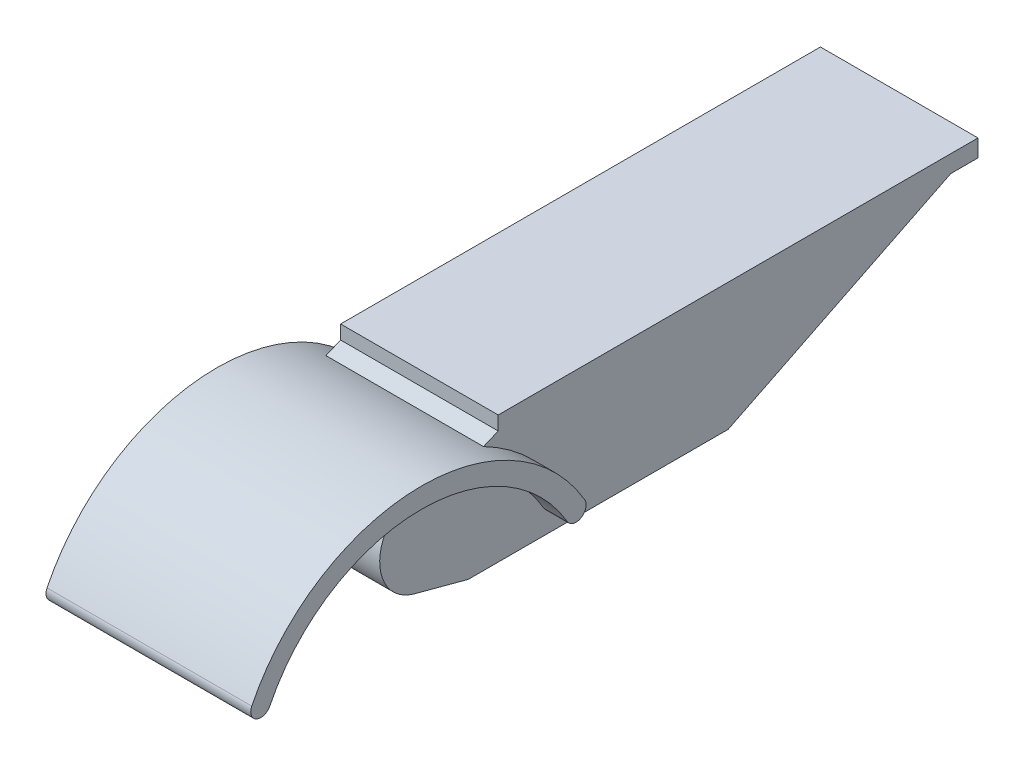
SolidWorks part; units mm, degrees
ref_plane "Front Plane" through (0, 0, 0) normal (0, 0, 1) x (1, 0, 0)
ref_plane "Top Plane" through (0, 0, 0) normal (0, 1, 0) x (1, 0, 0)
ref_plane "Right Plane" through (0, 0, 0) normal (1, 0, 0) x (0, 0, -1)
sketch "Sketch1" plane through (0, 0, 0) normal (1, 0, 0) x (0, 0, -1)
  line L0 (-4.9707, 0.2393) -> (17.4289, 0.2393)
  line L1 (-7.8233, 14.2353) -> (40.513, 14.2353)
  line L2 (-10.8379, 1.3954) -> (15.3495, 1.3954)
  line L3 (-18.9137, 0.2393) -> (-18.9137, 4.7001)
  line L4 (-18.9137, 0.2393) -> (-4.9707, 0.2393)
  line L5 (-16.2784, 2.8532) -> (-10.8379, 1.3954)
  line L6 (-6.6428, 1.6116) -> (-6.2905, 1.0013)
  line L7 (0, -1.5999) -> (0, 2.9721)
  line L8 (-2.1082, 1.3723) -> (-2.1082, 0)
  line L9 (-15.0622, 12.0911) -> (-9.6013, 12.0911)
  line L12 (-7.8233, 14.2353) -> (-7.8233, 12.8355)
  line L13 (-7.8233, 12.8355) -> (-9.6013, 12.0911)
  line L14 (17.4289, 0.2393) -> (26.0442, 0.2393)
  line L15 (37.7662, 12.4952) -> (15.3495, 1.3954)
  line L16 (15.9056, 1.8141) -> (26.0442, 1.8141)
  line L17 (2.1082, 1.3723) -> (2.1082, 0)
  line L18 (17.8816, 1.5748) -> (17.8816, 0)
  line L19 (19.9898, -1.5999) -> (19.9898, 2.9721)
  line L20 (22.098, 1.5748) -> (22.098, 0)
  line L23 (26.0442, 1.8141) -> (26.0442, 0.2393)
  line L24 (40.513, 14.2353) -> (40.513, 12.4952)
  line L25 (37.7662, 14.0192) -> (37.7662, 12.4952)
  line L26 (37.7662, 12.4952) -> (40.513, 12.4952)
  arc A0 (-1.4853, 4.8568) -> (-35.0245, 3.6228) centre (-17.9234, -4.7709) ccw
  arc A1 (-3.2391, 3.8296) -> (-33.1999, 2.7272) centre (-17.9234, -4.7709) ccw
  arc A2 (-35.0245, 3.6228) -> (-33.1999, 2.7272) centre (-34.1122, 3.175) ccw
  arc A3 (-3.2391, 3.8296) -> (-1.4853, 4.8568) centre (-2.3622, 4.3432) ccw
  arc A4 (-15.0622, 12.0911) -> (-16.2784, 2.8532) centre (-15.0622, 7.3921) ccw
  arc A6 (-6.2905, 1.0013) -> (-4.9707, 0.2393) centre (-4.9707, 1.7634) ccw
  circle A7 centre (-15.0622, 7.3921) radius 1.7526
  arc A8 (3.6624, -0.0001) -> (5.1632, 1.2593) centre (3.6624, 1.5238) ccw
  arc A9 (15.9144, 1.9346) -> (17.4289, 0.2393) centre (17.4289, 1.7634) ccw
  circle A10 centre (10.9474, 6.4523) radius 1.7526
  dimension "D1" = 19.05
  dimension "D2" = 34.1122
  dimension "D3" = 1.0162
  dimension "D5" = 4.699
  dimension "D6" = 26.0096
  dimension "D11" = 3.5052
  dimension "D4" = 44.9579
  dimension "D7" = 13.996
  dimension "D8" = 19.9898
  dimension "D9" = 26.343
  dimension "D10" = 15
  dimension "D12" = 34.2596
  dimension "D13" = 3.175
  dimension "D14" = 4.3432
  dimension "D15" = 2.3622
  dimension "D16" = 55.5752
  dimension "D17" = 19.05
  dimension "D18" = 15.0622
sketch "Sketch2" plane through (0, 0, 0) normal (0, 1, 0) x (1, 0, 0)
  line L0 (44.7137, -7.1143) -> (49.2857, -7.1143)
  line L1 (37.626, -13.1518) -> (83.307, -13.1518)
  line L2 (37.626, -1.1631) -> (83.307, -1.1631)
  line L3 (83.307, -14.6759) -> (25.6626, -14.6759)
  line L4 (83.307, 0.3609) -> (25.6626, 0.3609)
  line L5 (39.9673, -17.4938) -> (13.0358, -18.158)
  line L6 (39.9674, 3.011) -> (13.0358, 3.6753)
  line L7 (39.9171, 0.9797) -> (12.9852, 1.644)
  line L8 (39.917, -15.4624) -> (12.9851, -16.1267)
  line L9 (9.7303, -14.9331) -> (9.7303, 0.4503)
  line L10 (11.762, -14.9333) -> (11.762, 0.4506)
  line L11 (46.9997, -9.4003) -> (46.9997, -4.8283)
  line L12 (37.626, -14.6759) -> (37.626, 0.3609)
  line L13 (26.5231, -12.8927) -> (26.5231, -1.3358)
  line L14 (25.6626, -13.1518) -> (37.626, -13.1518)
  line L15 (26.5231, -11.3179) -> (37.5756, -11.3179)
  line L16 (37.6244, -12.8927) -> (26.5231, -12.8927)
  line L17 (28.8345, -11.3179) -> (28.8345, -12.8927)
  line L18 (25.6626, -13.1518) -> (25.6626, -14.6759)
  line L19 (32.1873, -11.3179) -> (32.1873, -12.8927)
  line L20 (25.6626, -1.1631) -> (37.626, -1.1631)
  line L21 (26.5231, -2.9106) -> (37.6244, -2.9106)
  line L22 (37.6244, -1.3358) -> (26.5231, -1.3358)
  line L23 (25.6626, -1.1631) -> (25.6626, 0.3609)
  line L24 (28.8345, -2.9106) -> (28.8345, -1.3358)
  line L25 (32.1873, -2.9106) -> (32.1873, -1.3358)
  line L26 (66.9895, -9.4003) -> (66.9895, -4.8283)
  line L27 (64.7035, -7.1143) -> (69.2755, -7.1143)
  line L28 (83.307, -13.1518) -> (83.307, -14.6759)
  line L29 (83.307, -1.1631) -> (83.307, 0.3609)
  circle A0 centre (46.9997, -7.1143) radius 2.1082
  arc A1 (9.7303, -14.9331) -> (13.0358, -18.158) centre (12.9562, -14.9331) ccw
  arc A2 (11.762, -14.9333) -> (12.9851, -16.1267) centre (12.9557, -14.9333) ccw
  arc A3 (13.0358, 3.6753) -> (9.7303, 0.4503) centre (12.9563, 0.4503) ccw
  arc A4 (12.9852, 1.644) -> (11.762, 0.4506) centre (12.9557, 0.4506) ccw
  arc A5 (39.9673, -17.4938) -> (43.0786, -14.7418) centre (39.8877, -14.2691) ccw
  arc A6 (39.917, -15.4624) -> (41.01, -14.6759) centre (39.8876, -14.2689) ccw
  arc A7 (43.0619, 0.3609) -> (39.9674, 3.011) centre (39.8879, -0.2136) ccw
  arc A8 (40.9827, 0.2617) -> (39.9171, 0.9797) centre (39.8877, -0.2138) ccw
  circle A9 centre (66.9895, -7.1143) radius 2.1082
  arc A10 (83.307, -14.6759) -> (55.3437, -14.6767) centre (69.3251, -7.158) ccw
  arc A11 (55.3437, -14.6767) -> (83.307, 0.3609) centre (69.3253, -7.1579) ccw
sketch "Sketch3" plane through (0, 0, 0) normal (1, 0, 0) x (0, 0, -1)
  line L0 (40.513, 14.2353) -> (40.513, 12.4952) construction
  line L1 (-7.8233, 14.2353) -> (40.513, 14.2353) construction
  line L2 (-7.8233, 14.2353) -> (-7.8233, 12.8355) construction
  line L3 (-7.8233, 12.8355) -> (-9.6013, 12.0911) construction
  line L4 (-15.0622, 12.0911) -> (-9.6013, 12.0911) construction
  line L5 (-16.2784, 2.8532) -> (-10.8379, 1.3954) construction
  line L6 (-10.8379, 1.3954) -> (15.3495, 1.3954) construction
  line L7 (37.7662, 12.4952) -> (15.3495, 1.3954) construction
  line L8 (37.7662, 12.4952) -> (40.513, 12.4952) construction
  line L9 (40.513, 14.2353) -> (40.513, 12.4952)
  line L10 (-7.8233, 14.2353) -> (40.513, 14.2353)
  line L11 (-7.8233, 14.2353) -> (-7.8233, 12.8355)
  line L12 (-7.8233, 12.8355) -> (-9.6013, 12.0911)
  line L13 (-15.0622, 12.0911) -> (-9.6013, 12.0911)
  line L14 (-16.2784, 2.8532) -> (-10.8379, 1.3954)
  line L15 (-10.8379, 1.3954) -> (15.3495, 1.3954)
  line L16 (37.7662, 12.4952) -> (15.3495, 1.3954)
  line L17 (37.7662, 12.4952) -> (40.513, 12.4952)
  arc A0 (-15.0622, 12.0911) -> (-16.2784, 2.8532) centre (-15.0622, 7.3921) ccw construction
  arc A1 (-15.0622, 12.0911) -> (-16.2784, 2.8532) centre (-15.0622, 7.3921) ccw
extrude "Boss-Extrude1" add sketch "Sketch3" along normal mid plane 15.875
sketch "Sketch4" plane through (0, 0, 0) normal (1, 0, 0) x (0, 0, -1)
  arc A0 (-3.2391, 3.8296) -> (-1.4853, 4.8568) centre (-2.3622, 4.3432) ccw construction
  arc A1 (-1.4853, 4.8568) -> (-35.0245, 3.6228) centre (-17.9234, -4.7709) ccw construction
  arc A2 (-35.0245, 3.6228) -> (-33.1999, 2.7272) centre (-34.1122, 3.175) ccw construction
  arc A3 (-3.2391, 3.8296) -> (-33.1999, 2.7272) centre (-17.9234, -4.7709) ccw construction
  arc A4 (-3.2391, 3.8296) -> (-1.4853, 4.8568) centre (-2.3622, 4.3432) ccw
  arc A5 (-1.4853, 4.8568) -> (-35.0245, 3.6228) centre (-17.9234, -4.7709) ccw
  arc A6 (-35.0245, 3.6228) -> (-33.1999, 2.7272) centre (-34.1122, 3.175) ccw
  arc A7 (-3.2391, 3.8296) -> (-33.1999, 2.7272) centre (-17.9234, -4.7709) ccw
extrude "Boss-Extrude2" add sketch "Sketch4" along normal mid plane 20.6248
